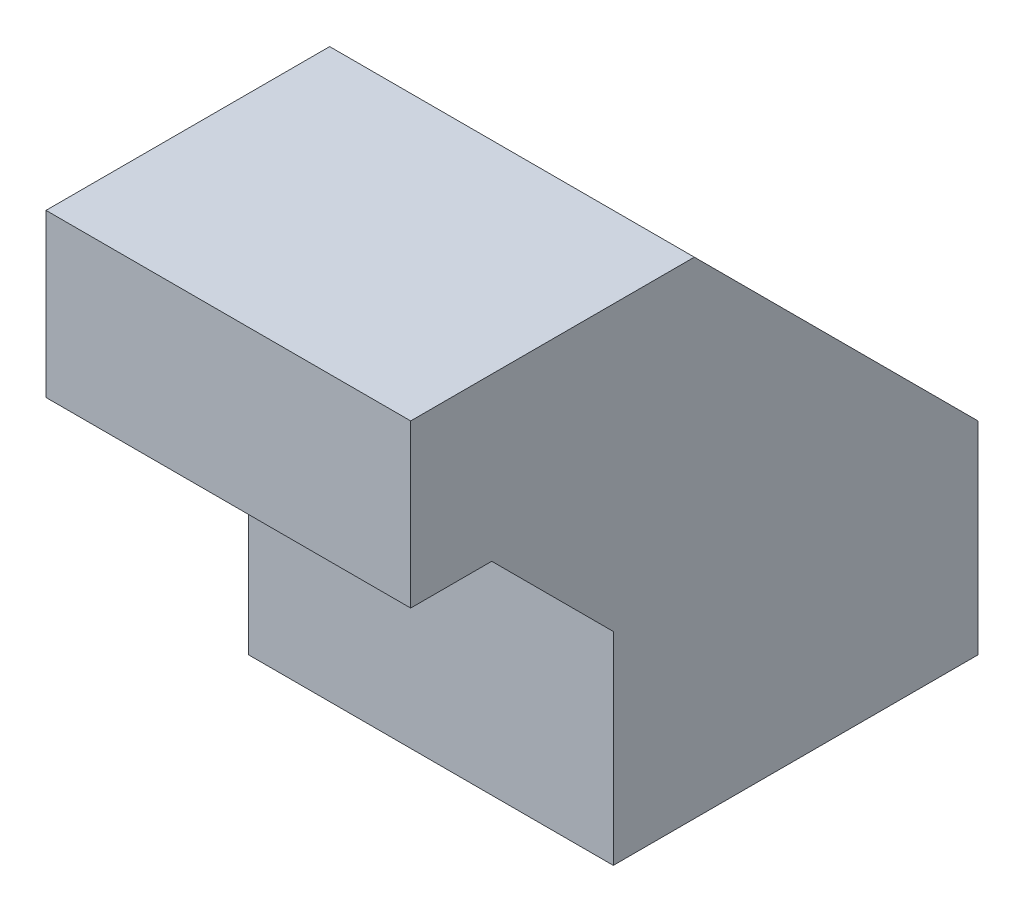
SolidWorks part; units mm, degrees
ref_plane "Front Plane" through (0, 0, 0) normal (0, 0, 1) x (1, 0, 0)
ref_plane "Top Plane" through (0, 0, 0) normal (0, 1, 0) x (1, 0, 0)
ref_plane "Right Plane" through (0, 0, 0) normal (1, 0, 0) x (0, 0, -1)
sketch "Sketch1" plane through (0, 0, 0) normal (0, 1, 0) x (1, 0, 0)
  line L1 (-22.5, 22.5) -> (22.5, 22.5)
  line L2 (-22.5, 22.5) -> (-22.5, -22.5)
  line L3 (-22.5, -22.5) -> (22.5, -22.5)
  line L4 (22.5, 22.5) -> (22.5, -22.5)
  line L5 (-22.5, 22.5) -> (22.5, -22.5) construction
  line L6 (-22.5, -22.5) -> (22.5, 22.5) construction
  point P0 (0, 0)
  dimension "D1" = 45
  dimension "D2" = 45
extrude "Boss-Extrude1" add sketch "Sketch1" along normal blind 40
sketch "Sketch2" plane through (0, 40, 0) normal (0, 1, 0) x (1, 0, 0)
  line L1 (-22.5, 22.5) -> (22.5, 22.5)
  line L2 (-22.5, 22.5) -> (-22.5, -47.5)
  line L3 (-22.5, -47.5) -> (22.5, -47.5)
  line L4 (22.5, 22.5) -> (22.5, -47.5)
  dimension "D1" = 45
  dimension "D2" = 70
extrude "Boss-Extrude2" add sketch "Sketch2" along normal blind 20
chamfer "Chamfer1" distance 15 angle 45 1 edges
chamfer "Chamfer2" distance 35 angle 45 1 edges at (0, 60, -22.5)
sketch "Sketch3" plane through (0, 0, 0) normal (0, 1, 0) x (1, 0, 0)
  circle A0 centre (0, 0) radius 20
  dimension "D1" = 40
extrude "Cut-Extrude1" cut sketch "Sketch3" along normal blind 25
ref_plane "Plane1" through (0, 0, 0) normal (0, 0.7071, 0.7071) x (-1, 0, 0)
ref_plane "Plane2" through (0, 1.4142, 1.4142) normal (0, 0.7071, 0.7071) x (-1, 0, 0)
sketch "Sketch4" plane through (0, 1.4142, 1.4142) normal (0, 0.7071, 0.7071) x (-1, 0, 0)
  line L0 (0, 33) -> (0, -33) construction
  line L1 (-20, -11.5876) -> (20, -11.5876)
  line L2 (-20, -11.5876) -> (-20, -31.5876)
  line L3 (-20, -31.5876) -> (20, -31.5876)
  line L4 (20, -11.5876) -> (20, -31.5876)
  line L5 (-22.5, -33.5876) -> (22.5, -33.5876) construction
  dimension "D1" = 20
  dimension "D2" = 40
  dimension "D3" = 20
  dimension "D4" = 2
extrude "Cut-Extrude2" cut sketch "Sketch4" along normal blind 49
